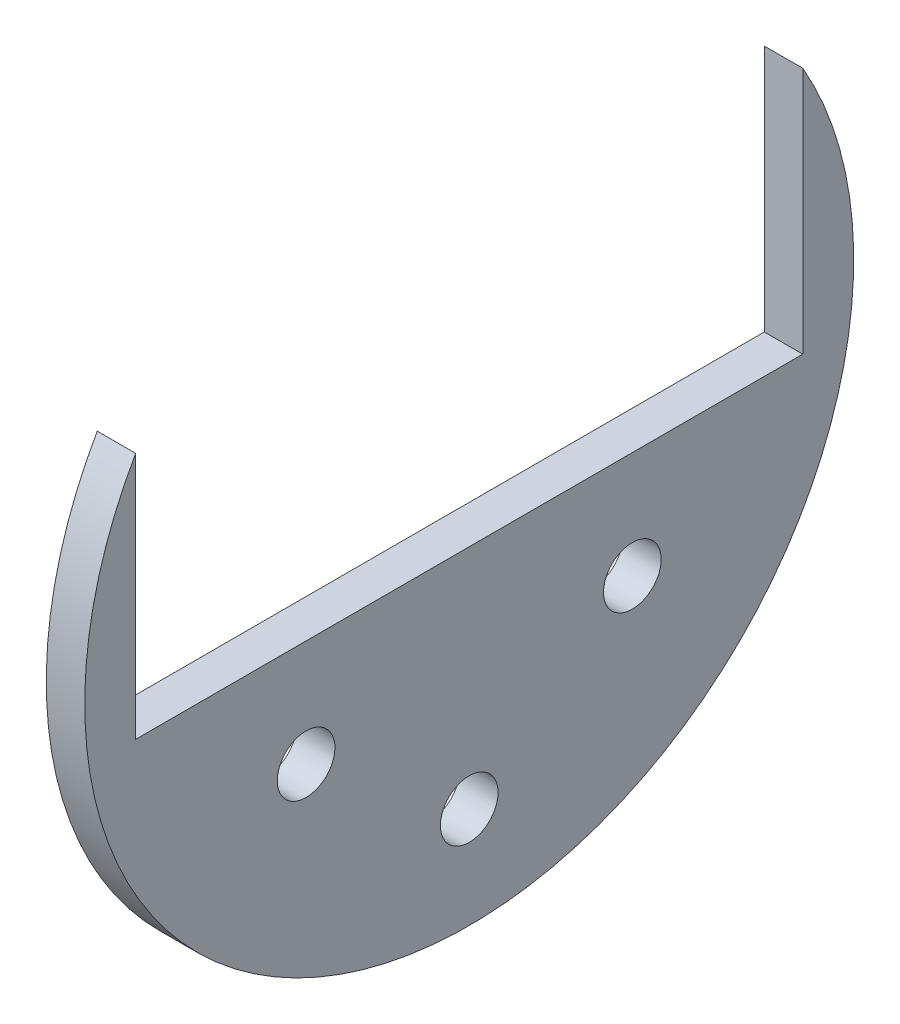
SolidWorks part; units mm, degrees
ref_plane "Front Plane" through (0, 0, 0) normal (0, 0, 1) x (1, 0, 0)
ref_plane "Top Plane" through (0, 0, 0) normal (0, 1, 0) x (1, 0, 0)
ref_plane "Right Plane" through (0, 0, 0) normal (1, 0, 0) x (0, 0, -1)
sketch "Sketch1" plane through (0, 0, 0) normal (1, 0, 0) x (0, 0, -1)
  line L0 (0, 0) -> (0, 14.75) construction
  line L1 (0, 14.75) -> (-8.4853, 8.4853) construction
  line L2 (-8.4853, 8.4853) -> (-14.75, 0) construction
  line L3 (0, 0) -> (-8.4853, 8.4853) construction
  circle A0 centre (0, 0) radius 20
  circle A1 centre (0, 0) radius 14.75
  circle A2 centre (0, 0) radius 12
  circle A3 centre (0, 14.75) radius 1.5
  circle A4 centre (14.75, 0) radius 1.5
  circle A5 centre (0, -14.75) radius 1.5
  circle A6 centre (-14.75, 0) radius 1.5
  circle A7 centre (-8.4853, 8.4853) radius 1.5
  circle A8 centre (8.4853, 8.4853) radius 1.5
  circle A9 centre (8.4853, -8.4853) radius 1.5
  circle A10 centre (-8.4853, -8.4853) radius 1.5
  dimension "D1" = 29.5
  dimension "D2" = 40
  dimension "D3" = 24
  dimension "D4" = 4
  dimension "D6" = 4
  dimension "D5" = 14.75
  dimension "D7" = 12
extrude "Boss-Extrude1" add sketch "Sketch1" along normal blind 2 contours A0 A6 A1 A3 A4 A5 | A6 A1 A5 A4 A3 A10 A2 A7 A8 A9 | A10 A2 A9 A8 A7
sketch "Sketch3" plane through (2, 0, 0) normal (1, 0, 0) x (0, 0, -1)
  line L4 (-16.75, 16.75) -> (-16.75, -2.3335)
  line L5 (-16.75, -2.3335) -> (16.75, -2.3335)
  line L6 (16.75, -2.3335) -> (16.75, 16.75)
  line L7 (16.75, 16.75) -> (-16.75, 16.75)
  line L8 (-16.75, 16.75) -> (-16.75, -2.3335) construction
  line L9 (-16.75, -2.3335) -> (16.75, -2.3335) construction
  line L10 (16.75, -2.3335) -> (16.75, 16.75) construction
  line L11 (16.75, 16.75) -> (-16.75, 16.75) construction
  line L16 (-17.35, 17.35) -> (-17.35, -2.9335)
  line L17 (-17.35, -2.9335) -> (17.35, -2.9335)
  line L18 (17.35, -2.9335) -> (17.35, 17.35)
  line L19 (17.35, 17.35) -> (-17.35, 17.35)
  line L20 (-17.35, 17.35) -> (-17.35, -2.9335)
  line L21 (-17.35, -2.9335) -> (17.35, -2.9335)
  line L22 (17.35, -2.9335) -> (17.35, 17.35)
  line L23 (17.35, 17.35) -> (-17.35, 17.35)
  dimension "D1" = 0
  dimension "D2" = 0.6
extrude "Cut-Extrude1" cut sketch "Sketch3" against normal through all
